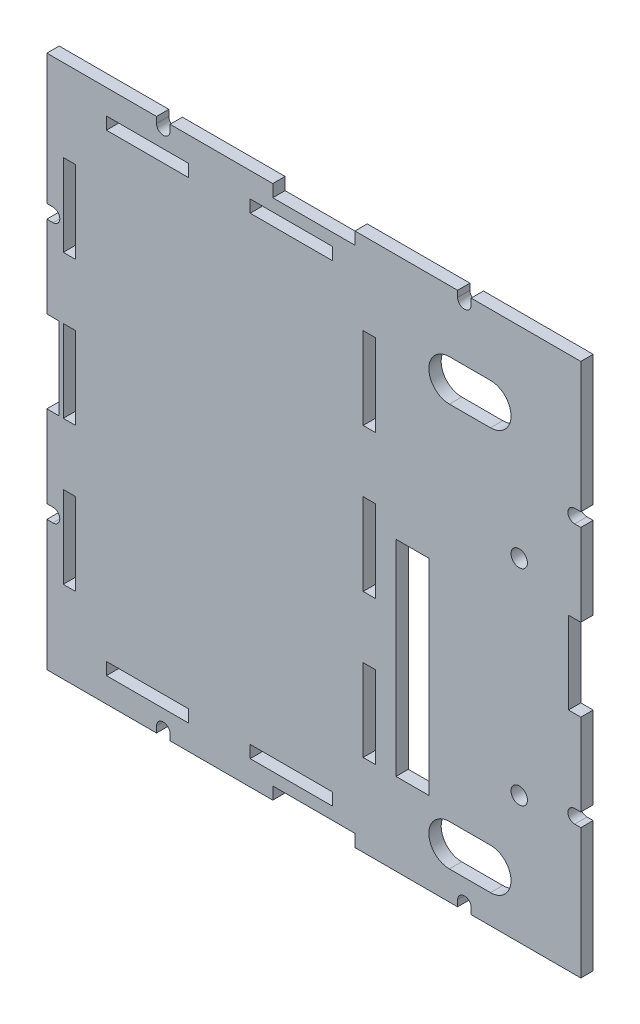
SolidWorks part; units mm, degrees
ref_plane "Front Plane" through (0, 0, 0) normal (0, 0, 1) x (1, 0, 0)
ref_plane "Top Plane" through (0, 0, 0) normal (0, 1, 0) x (1, 0, 0)
ref_plane "Right Plane" through (0, 0, 0) normal (1, 0, 0) x (0, 0, -1)
sketch "Sketch1" plane through (0, 0, 0) normal (0, 0, 1) x (1, 0, 0)
  line L0 (55, 0) -> (-55, 0) construction
  line L1 (65, -65) -> (-65, -65)
  line L2 (65, -65) -> (65, 65)
  line L3 (65, 65) -> (-65, 65)
  line L4 (-65, -65) -> (-65, 65)
  line L5 (65, -65) -> (-65, 65) construction
  line L6 (65, 65) -> (-65, -65) construction
  line L7 (10, 62) -> (-10, 62)
  line L8 (10, 62) -> (10, 65)
  line L9 (10, 65) -> (-10, 65)
  line L10 (-10, 62) -> (-10, 65)
  line L11 (10, 62) -> (-10, 65) construction
  line L12 (10, 65) -> (-10, 62) construction
  line L13 (-62, -10) -> (-65, -10)
  line L14 (-62, -10) -> (-62, 10)
  line L15 (-62, 10) -> (-65, 10)
  line L16 (-65, -10) -> (-65, 10)
  line L17 (-62, -10) -> (-65, 10) construction
  line L18 (-62, 10) -> (-65, -10) construction
  line L19 (10, -65) -> (-10, -65)
  line L20 (-10, -62) -> (-10, -65)
  line L21 (10, -62) -> (-10, -62)
  line L22 (10, -62) -> (10, -65)
  line L23 (0, -55) -> (0, 55) construction
  line L24 (62, 10) -> (65, 10)
  line L25 (65, -10) -> (65, 10)
  line L26 (62, -10) -> (65, -10)
  line L27 (62, -10) -> (62, 10)
  line L28 (-36.65, 63.5) -> (-36.65, 66.5) construction
  line L29 (-38.3, 63.5) -> (-38.3, 66.5)
  line L30 (-35, 63.5) -> (-35, 66.5)
  line L31 (-63.5, 31.65) -> (-66.5, 31.65) construction
  line L32 (-63.5, 30) -> (-66.5, 30)
  line L33 (-63.5, 33.3) -> (-66.5, 33.3)
  line L34 (36.65, 63.5) -> (36.65, 66.5) construction
  line L35 (38.3, 63.5) -> (38.3, 66.5)
  line L36 (35, 63.5) -> (35, 66.5)
  line L37 (63.5, 31.65) -> (66.5, 31.65) construction
  line L38 (63.5, 30) -> (66.5, 30)
  line L39 (63.5, 33.3) -> (66.5, 33.3)
  line L40 (63.5, -31.65) -> (66.5, -31.65) construction
  line L41 (63.5, -30) -> (66.5, -30)
  line L42 (63.5, -33.3) -> (66.5, -33.3)
  line L43 (36.65, -63.5) -> (36.65, -66.5) construction
  line L44 (38.3, -63.5) -> (38.3, -66.5)
  line L45 (35, -63.5) -> (35, -66.5)
  line L46 (-36.65, -63.5) -> (-36.65, -66.5) construction
  line L47 (-38.3, -63.5) -> (-38.3, -66.5)
  line L48 (-35, -63.5) -> (-35, -66.5)
  line L49 (-63.5, -31.65) -> (-66.5, -31.65) construction
  line L50 (-63.5, -30) -> (-66.5, -30)
  line L51 (-63.5, -33.3) -> (-66.5, -33.3)
  line L52 (-58, -45) -> (-61, -45)
  line L53 (-58, -10) -> (-61, -10)
  line L54 (-58, -10) -> (-58, 10)
  line L55 (-58, 10) -> (-61, 10)
  line L56 (-61, -10) -> (-61, 10)
  line L57 (-58, -10) -> (-61, 10) construction
  line L58 (-58, 10) -> (-61, -10) construction
  line L59 (-58, 25) -> (-61, 25)
  line L60 (-58, 25) -> (-58, 45)
  line L61 (-58, 45) -> (-61, 45)
  line L62 (-61, 25) -> (-61, 45)
  line L63 (-58, 25) -> (-61, 45) construction
  line L64 (-58, 45) -> (-61, 25) construction
  line L65 (-61, -25) -> (-61, -45)
  line L66 (-58, -25) -> (-61, -25)
  line L67 (-58, -25) -> (-58, -45)
  line L68 (-15.5, -59) -> (4.5, -59)
  line L69 (-30.5, 56) -> (-50.5, 56)
  line L70 (-30.5, 56) -> (-30.5, 59)
  line L71 (-30.5, 59) -> (-50.5, 59)
  line L72 (-50.5, 56) -> (-50.5, 59)
  line L73 (-30.5, 56) -> (-50.5, 59) construction
  line L74 (-30.5, 59) -> (-50.5, 56) construction
  line L75 (-15.5, 56) -> (4.5, 56)
  line L76 (-15.5, 56) -> (-15.5, 59)
  line L77 (-15.5, 59) -> (4.5, 59)
  line L78 (4.5, 56) -> (4.5, 59)
  line L79 (-15.5, 56) -> (4.5, 59) construction
  line L80 (-15.5, 59) -> (4.5, 56) construction
  line L81 (4.5, -56) -> (4.5, -59)
  line L82 (-15.5, -56) -> (4.5, -56)
  line L83 (-15.5, -56) -> (-15.5, -59)
  line L84 (-30.5, -59) -> (-50.5, -59)
  line L85 (-50.5, -56) -> (-50.5, -59)
  line L86 (-30.5, -56) -> (-50.5, -56)
  line L87 (-30.5, -56) -> (-30.5, -59)
  line L88 (43, -53) -> (33, -53) construction
  line L89 (12, 45) -> (15, 45)
  line L90 (12, 45) -> (12, 25)
  line L91 (12, 25) -> (15, 25)
  line L92 (15, 45) -> (15, 25)
  line L93 (12, 45) -> (15, 25) construction
  line L94 (12, 25) -> (15, 45) construction
  line L95 (15, -10) -> (12, -10)
  line L96 (15, -10) -> (15, 10)
  line L97 (15, 10) -> (12, 10)
  line L98 (12, -10) -> (12, 10)
  line L99 (15, -10) -> (12, 10) construction
  line L100 (15, 10) -> (12, -10) construction
  line L101 (12, -45) -> (15, -45)
  line L102 (12, -45) -> (12, -25)
  line L103 (12, -25) -> (15, -25)
  line L104 (15, -45) -> (15, -25)
  line L105 (12, -45) -> (15, -25) construction
  line L106 (12, -25) -> (15, -45) construction
  line L107 (28, -45) -> (20, -45)
  line L108 (28, -45) -> (28, 5)
  line L109 (28, 5) -> (20, 5)
  line L110 (20, -45) -> (20, 5)
  line L111 (28, -45) -> (20, 5) construction
  line L112 (28, 5) -> (20, -45) construction
  line L117 (43, 45) -> (33, 45) construction
  line L118 (43, 40) -> (33, 40)
  line L119 (43, 50) -> (33, 50)
  line L120 (43, -48) -> (33, -48)
  line L121 (43, -58) -> (33, -58)
  arc A0 (-38.3, 63.5) -> (-35, 63.5) centre (-36.65, 63.5) ccw
  arc A1 (-35, 66.5) -> (-38.3, 66.5) centre (-36.65, 66.5) ccw
  arc A2 (-63.5, 30) -> (-63.5, 33.3) centre (-63.5, 31.65) ccw
  arc A3 (-66.5, 33.3) -> (-66.5, 30) centre (-66.5, 31.65) ccw
  arc A4 (38.3, 63.5) -> (35, 63.5) centre (36.65, 63.5) cw
  arc A5 (35, 66.5) -> (38.3, 66.5) centre (36.65, 66.5) cw
  arc A6 (63.5, 30) -> (63.5, 33.3) centre (63.5, 31.65) cw
  arc A7 (66.5, 33.3) -> (66.5, 30) centre (66.5, 31.65) cw
  arc A8 (63.5, -30) -> (63.5, -33.3) centre (63.5, -31.65) ccw
  arc A9 (66.5, -33.3) -> (66.5, -30) centre (66.5, -31.65) ccw
  arc A10 (38.3, -63.5) -> (35, -63.5) centre (36.65, -63.5) ccw
  arc A11 (35, -66.5) -> (38.3, -66.5) centre (36.65, -66.5) ccw
  arc A12 (-38.3, -63.5) -> (-35, -63.5) centre (-36.65, -63.5) cw
  arc A13 (-35, -66.5) -> (-38.3, -66.5) centre (-36.65, -66.5) cw
  arc A14 (-63.5, -30) -> (-63.5, -33.3) centre (-63.5, -31.65) cw
  arc A15 (-66.5, -33.3) -> (-66.5, -30) centre (-66.5, -31.65) cw
  arc A20 (43, 40) -> (43, 50) centre (43, 45) ccw
  arc A21 (33, 50) -> (33, 40) centre (33, 45) ccw
  circle A22 centre (50, 16) radius 2
  circle A23 centre (50, -34) radius 2
  arc A24 (43, -48) -> (43, -58) centre (43, -53) cw
  arc A25 (33, -58) -> (33, -48) centre (33, -53) cw
  point P0 (0, 0)
  point P6 (0, 63.5)
  point P11 (-63.5, 0)
  point P16 (-36.65, 65)
  point P35 (-65, 31.65)
  point P42 (-59.5, 35)
  point P45 (36.65, 65)
  point P52 (65, 31.65)
  point P59 (65, -31.65)
  point P66 (36.65, -65)
  point P73 (-36.65, -65)
  point P80 (-65, -31.65)
  point P85 (-59.5, 0)
  point P94 (-5.5, 57.5)
  point P100 (-40.5, 57.5)
  point P108 (13.5, -35)
  point P117 (13.5, 35)
  point P123 (13.5, 0)
  point P132 (24, -20)
  point P138 (38, -53)
  point P143 (38, 45)
  dimension "D7" = 1.65
  dimension "D10" = 1.65
  dimension "D29" = 10
  dimension "D31" = 5
  dimension "D35" = 4
  dimension "D1" = 130
  dimension "D2" = 130
  dimension "D3" = 20
  dimension "D4" = 3
  dimension "D5" = 20
  dimension "D6" = 3
  dimension "D8" = 3
  dimension "D9" = 25
  dimension "D11" = 3
  dimension "D12" = 20
  dimension "D13" = 20
  dimension "D14" = 3
  dimension "D15" = 15
  dimension "D16" = 4
  dimension "D17" = 20
  dimension "D18" = 3
  dimension "D19" = 6
  dimension "D20" = 15
  dimension "D21" = 10.5
  dimension "D22" = 10.5
  dimension "D23" = 3
  dimension "D24" = 20
  dimension "D25" = 15
  dimension "D26" = 15
  dimension "D27" = 50
  dimension "D28" = 8
  dimension "5" = 20
  dimension "D30" = 37
  dimension "D32" = 15
  dimension "D33" = 27
  dimension "D34" = 12
  dimension "D36" = 16
  dimension "D37" = 50
  dimension "D38" = 50
extrude "Boss-Extrude1" add sketch "Sketch1" along normal blind 3 contours L26 L27 L24 L2 L3 L8 L7 L10 L4 L15 L14 L13 L1 L20 L21 L22
